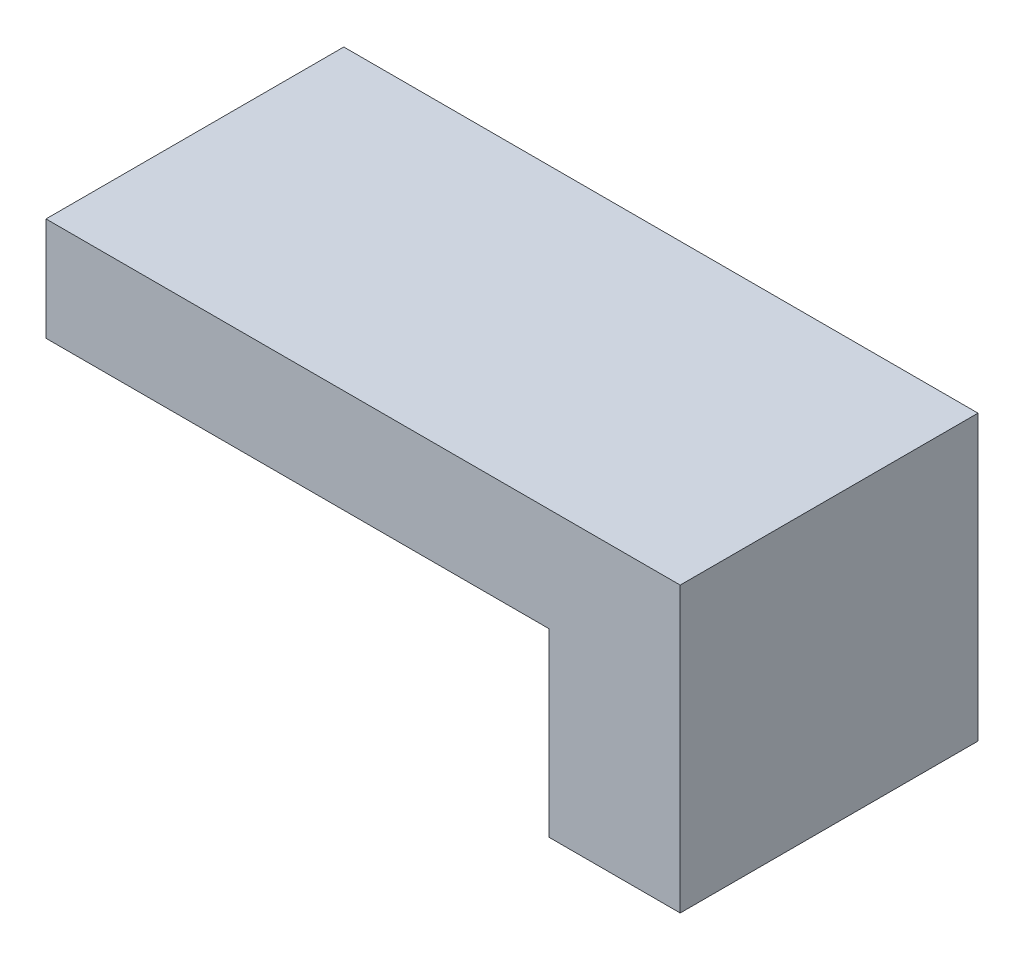
SolidWorks part; units mm, degrees
ref_plane "Front Plane" through (0, 0, 0) normal (0, 0, 1) x (1, 0, 0)
ref_plane "Top Plane" through (0, 0, 0) normal (0, 1, 0) x (1, 0, 0)
ref_plane "Right Plane" through (0, 0, 0) normal (1, 0, 0) x (0, 0, -1)
sketch "Sketch1" plane through (0, 0, 0) normal (0, 0, 1) x (1, 0, 0)
  line L0 (-23, 6.55) -> (-4.75, 6.55)
  line L1 (0, 10.3) -> (0, 0)
  line L3 (0, 0) -> (-4.75, 0)
  line L6 (-4.75, 0) -> (-4.75, 6.55)
  line L8 (-23, 6.55) -> (-23, 10.3)
  line L9 (-23, 10.3) -> (0, 10.3)
extrude "Boss-Extrude1" add sketch "Sketch1" along normal blind 10.8
